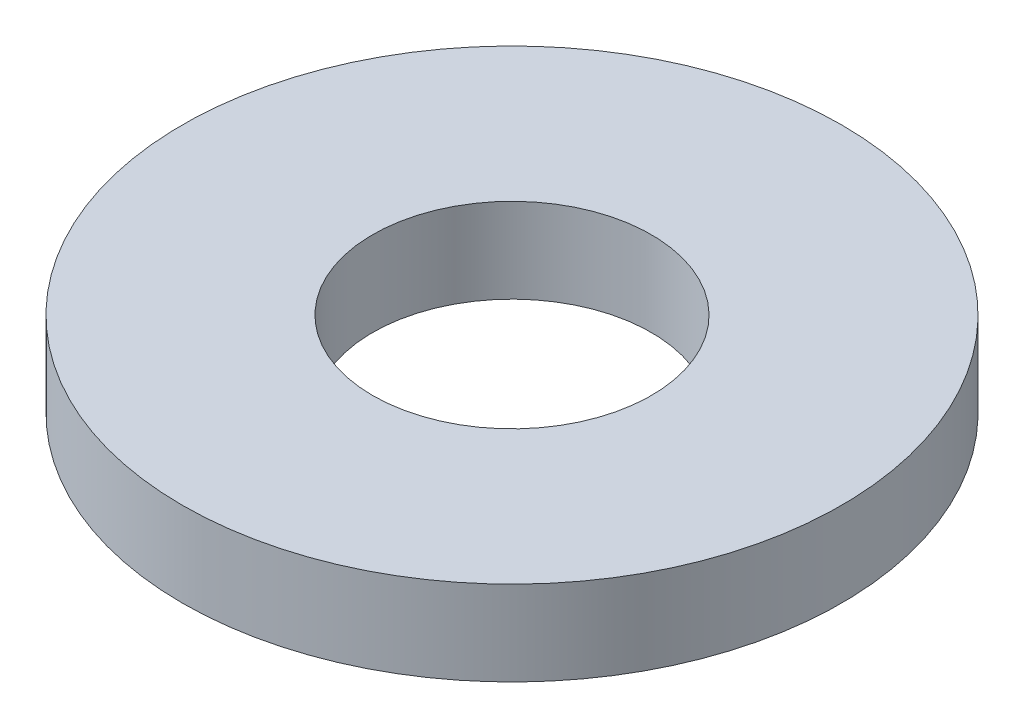
SolidWorks part; units mm, degrees
ref_plane "Спереди" through (0, 0, 0) normal (0, 0, 1) x (1, 0, 0)
ref_plane "Сверху" through (0, 0, 0) normal (0, 1, 0) x (1, 0, 0)
ref_plane "Справа" through (0, 0, 0) normal (1, 0, 0) x (0, 0, -1)
sketch "Эскиз2" plane through (0, 0, 0) normal (0, 1, 0) x (1, 0, 0)
  circle A0 centre (0, 0) radius 35
  circle A1 centre (0, 0) radius 14.8
extrude "Вытянуть1" add sketch "Эскиз2" along normal blind 9
